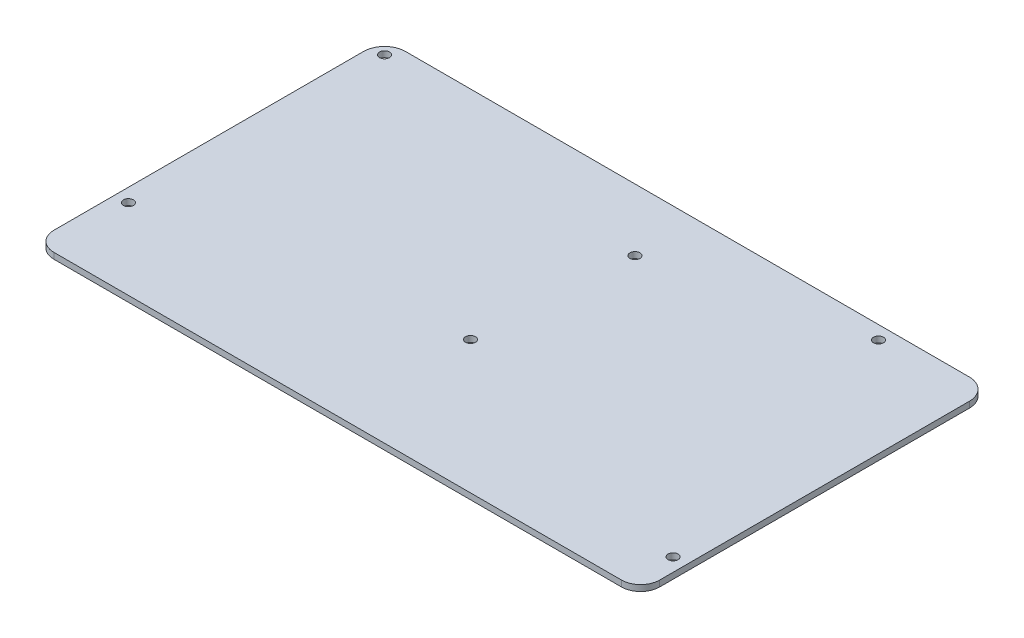
SolidWorks part; units mm, degrees
ref_plane "Front Plane" through (0, 0, 0) normal (0, 0, 1) x (1, 0, 0)
ref_plane "Top Plane" through (0, 0, 0) normal (0, 1, 0) x (1, 0, 0)
ref_plane "Right Plane" through (0, 0, 0) normal (1, 0, 0) x (0, 0, -1)
sketch "Sketch1" plane through (0, 0, 0) normal (0, 1, 0) x (1, 0, 0)
  line L1 (0, 0) -> (-201.28, 0)
  line L2 (0, 0) -> (0, 116.21)
  line L3 (0, 116.21) -> (-201.28, 116.21)
  line L4 (-201.28, 0) -> (-201.28, 116.21)
  circle A0 centre (-196.83, 26.67) radius 1.65
  circle A1 centre (-196.83, 111.76) radius 1.65
  circle A2 centre (-32.71, 111.76) radius 1.65
  circle A3 centre (-4.45, 15.24) radius 1.65
  circle A4 centre (-97.45, 95.57) radius 1.65
  circle A5 centre (-100.63, 44.13) radius 1.65
  dimension "D3" = 3.3
  dimension "D5" = 26.67
  dimension "D8" = 15.24
  dimension "D9" = 4.45
  dimension "D10" = 28.26
  dimension "D11" = 99.38
  dimension "D12" = 96.2
  dimension "D4" = 4.45
  dimension "D7" = 4.45
  dimension "D13" = 51.44
  dimension "D14" = 20.64
  dimension "D1" = 201.28
  dimension "D2" = 116.21
  dimension "D6" = 4.45
extrude "Boss-Extrude1" add sketch "Sketch1" along normal blind 2
fillet "Fillet1" radius 6.98 2 edges at (0, 1, -116.21) (-201.28, 1, -116.21)
fillet "Fillet2" radius 6.35 2 edges at (0, 1, 0) (-201.28, 1, 0)
